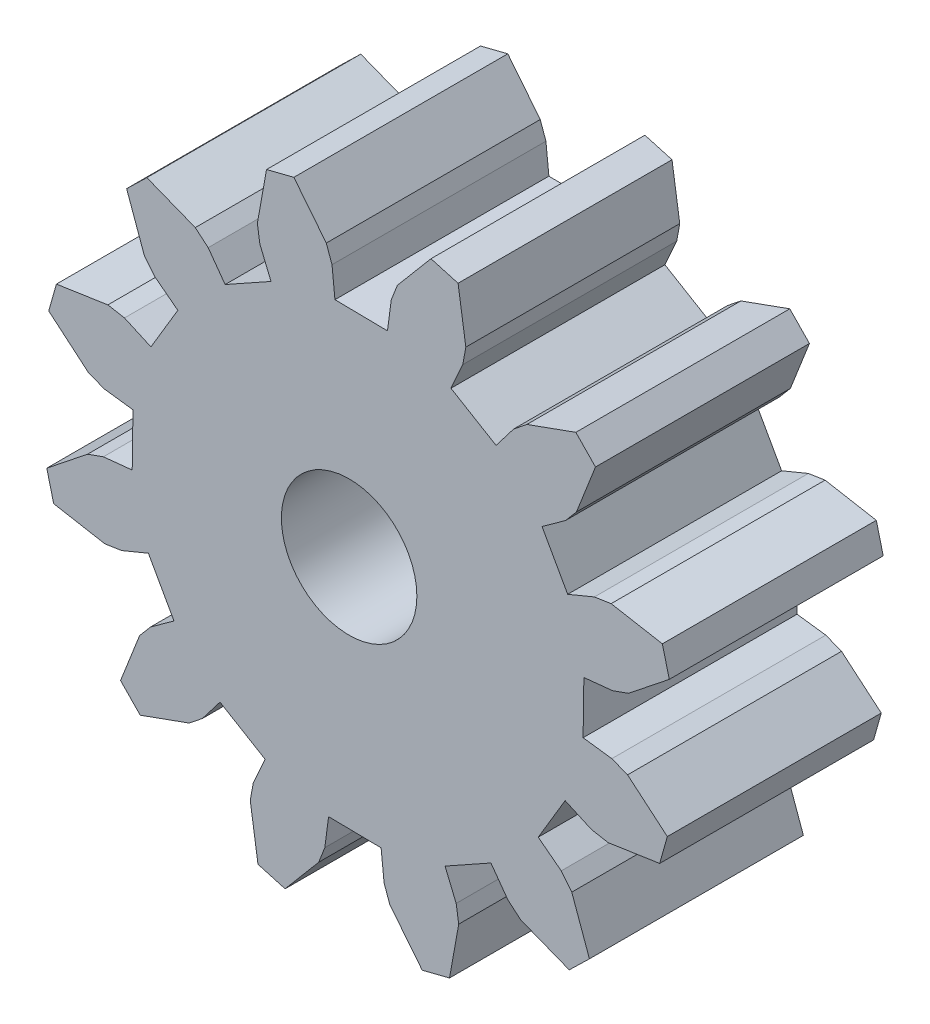
SolidWorks part; units mm, degrees
ref_plane "Front Plane" through (0, 0, 0) normal (0, 0, 1) x (1, 0, 0)
ref_plane "Top Plane" through (0, 0, 0) normal (0, 1, 0) x (1, 0, 0)
ref_plane "Right Plane" through (0, 0, 0) normal (1, 0, 0) x (0, 0, -1)
sketch "Model" plane through (0, 0, 0) normal (0, 0, 1) x (1, 0, 0)
  line L0 (3.2811, -0.5536) -> (3.684, -0.6063)
  line L1 (3.684, -0.6063) -> (3.9046, -0.6926)
  line L2 (3.9046, -0.6926) -> (4.4623, -1.1634)
  line L3 (4.4623, -1.1634) -> (4.3547, -1.5436)
  line L4 (4.3547, -1.5436) -> (3.6329, -1.652)
  line L5 (3.6329, -1.652) -> (3.3998, -1.6098)
  line L6 (3.3998, -1.6098) -> (3.0292, -1.4435)
  line L7 (3.0292, -1.4435) -> (2.6518, -2.0764)
  line L8 (2.6518, -2.0764) -> (2.9743, -2.3234)
  line L9 (2.9743, -2.3234) -> (3.1222, -2.5085)
  line L10 (3.1222, -2.5085) -> (3.3698, -3.195)
  line L11 (3.3698, -3.195) -> (3.0865, -3.4705)
  line L12 (3.0865, -3.4705) -> (2.4072, -3.2035)
  line L13 (2.4072, -3.2035) -> (2.2265, -3.0504)
  line L14 (2.2265, -3.0504) -> (1.9886, -2.7211)
  line L15 (1.9886, -2.7211) -> (1.3454, -3.0804)
  line L16 (1.3454, -3.0804) -> (1.5011, -3.4557)
  line L17 (1.5011, -3.4557) -> (1.5367, -3.6898)
  line L18 (1.5367, -3.6898) -> (1.4079, -4.4083)
  line L19 (1.4079, -4.4083) -> (1.0248, -4.5051)
  line L20 (1.0248, -4.5051) -> (0.57, -3.9343)
  line L21 (0.57, -3.9343) -> (0.49, -3.7113)
  line L22 (0.49, -3.7113) -> (0.4487, -3.3072)
  line L23 (0.4487, -3.3072) -> (-0.288, -3.2968)
  line L24 (-0.288, -3.2968) -> (-0.3408, -3.6996)
  line L25 (-0.3408, -3.6996) -> (-0.427, -3.9202)
  line L26 (-0.427, -3.9202) -> (-0.8978, -4.478)
  line L27 (-0.8978, -4.478) -> (-1.278, -4.3703)
  line L28 (-1.278, -4.3703) -> (-1.3865, -3.6485)
  line L29 (-1.3865, -3.6485) -> (-1.3443, -3.4154)
  line L30 (-1.3443, -3.4154) -> (-1.178, -3.0448)
  line L31 (-1.178, -3.0448) -> (-1.8108, -2.6674)
  line L32 (-1.8108, -2.6674) -> (-2.0579, -2.9899)
  line L33 (-2.0579, -2.9899) -> (-2.2429, -3.1378)
  line L34 (-2.2429, -3.1378) -> (-2.9295, -3.3855)
  line L35 (-2.9295, -3.3855) -> (-3.2049, -3.1021)
  line L36 (-3.2049, -3.1021) -> (-2.938, -2.4228)
  line L37 (-2.938, -2.4228) -> (-2.7849, -2.2421)
  line L38 (-2.7849, -2.2421) -> (-2.4555, -2.0042)
  line L39 (-2.4555, -2.0042) -> (-2.8149, -1.361)
  line L40 (-2.8149, -1.361) -> (-3.1901, -1.5168)
  line L41 (-3.1901, -1.5168) -> (-3.4243, -1.5523)
  line L42 (-3.4243, -1.5523) -> (-4.1427, -1.4235)
  line L43 (-4.1427, -1.4235) -> (-4.2396, -1.0404)
  line L44 (-4.2396, -1.0404) -> (-3.6687, -0.5856)
  line L45 (-3.6687, -0.5856) -> (-3.4458, -0.5056)
  line L46 (-3.4458, -0.5056) -> (-3.0416, -0.4643)
  line L47 (-3.0416, -0.4643) -> (-3.0312, 0.2724)
  line L48 (-3.0312, 0.2724) -> (-3.4341, 0.3252)
  line L49 (-3.4341, 0.3252) -> (-3.6547, 0.4114)
  line L50 (-3.6547, 0.4114) -> (-4.2124, 0.8822)
  line L51 (-4.2124, 0.8822) -> (-4.1048, 1.2624)
  line L52 (-4.1048, 1.2624) -> (-3.383, 1.3709)
  line L53 (-3.383, 1.3709) -> (-3.1499, 1.3287)
  line L54 (-3.1499, 1.3287) -> (-2.7792, 1.1624)
  line L55 (-2.7792, 1.1624) -> (-2.4019, 1.7952)
  line L56 (-2.4019, 1.7952) -> (-2.7244, 2.0423)
  line L57 (-2.7244, 2.0423) -> (-2.8723, 2.2273)
  line L58 (-2.8723, 2.2273) -> (-3.1199, 2.9139)
  line L59 (-3.1199, 2.9139) -> (-2.8366, 3.1893)
  line L60 (-2.8366, 3.1893) -> (-2.1573, 2.9224)
  line L61 (-2.1573, 2.9224) -> (-1.9765, 2.7693)
  line L62 (-1.9765, 2.7693) -> (-1.7387, 2.4399)
  line L63 (-1.7387, 2.4399) -> (-1.0955, 2.7993)
  line L64 (-1.0955, 2.7993) -> (-1.2512, 3.1745)
  line L65 (-1.2512, 3.1745) -> (-1.2868, 3.4087)
  line L66 (-1.2868, 3.4087) -> (-1.158, 4.1271)
  line L67 (-1.158, 4.1271) -> (-0.7749, 4.224)
  line L68 (-0.7749, 4.224) -> (-0.3201, 3.6531)
  line L69 (-0.3201, 3.6531) -> (-0.2401, 3.4302)
  line L70 (-0.2401, 3.4302) -> (-0.1987, 3.026)
  line L71 (-0.1987, 3.026) -> (0.538, 3.0156)
  line L72 (0.538, 3.0156) -> (0.5907, 3.4184)
  line L73 (0.5907, 3.4184) -> (0.677, 3.639)
  line L74 (0.677, 3.639) -> (1.1477, 4.1968)
  line L75 (1.1477, 4.1968) -> (1.5279, 4.0891)
  line L76 (1.5279, 4.0891) -> (1.6364, 3.3674)
  line L77 (1.6364, 3.3674) -> (1.5942, 3.1343)
  line L78 (1.5942, 3.1343) -> (1.4279, 2.7636)
  line L79 (1.4279, 2.7636) -> (2.0607, 2.3863)
  line L80 (2.0607, 2.3863) -> (2.3078, 2.7088)
  line L81 (2.3078, 2.7088) -> (2.4928, 2.8567)
  line L82 (2.4928, 2.8567) -> (3.1794, 3.1043)
  line L83 (3.1794, 3.1043) -> (3.4548, 2.821)
  line L84 (3.4548, 2.821) -> (3.1879, 2.1417)
  line L85 (3.1879, 2.1417) -> (3.0348, 1.9609)
  line L86 (3.0348, 1.9609) -> (2.7055, 1.7231)
  line L87 (2.7055, 1.7231) -> (3.0648, 1.0798)
  line L88 (3.0648, 1.0798) -> (3.44, 1.2356)
  line L89 (3.44, 1.2356) -> (3.6742, 1.2712)
  line L90 (3.6742, 1.2712) -> (4.3926, 1.1424)
  line L91 (4.3926, 1.1424) -> (4.4895, 0.7593)
  line L92 (4.4895, 0.7593) -> (3.9187, 0.3045)
  line L93 (3.9187, 0.3045) -> (3.6957, 0.2244)
  line L94 (3.6957, 0.2244) -> (3.2916, 0.1831)
  line L95 (3.2916, 0.1831) -> (3.2811, -0.5536)
extrude "Boss-Extrude1" add sketch "Model" along normal blind 3
sketch "Sketch2" plane through (0, 0, 3) normal (0, 0, 1) x (1, 0, 0)
  circle A0 centre (0, 0) radius 0.95
  dimension "D1" = 1.9
extrude "Cut-Extrude1" cut sketch "Sketch2" against normal blind 3
